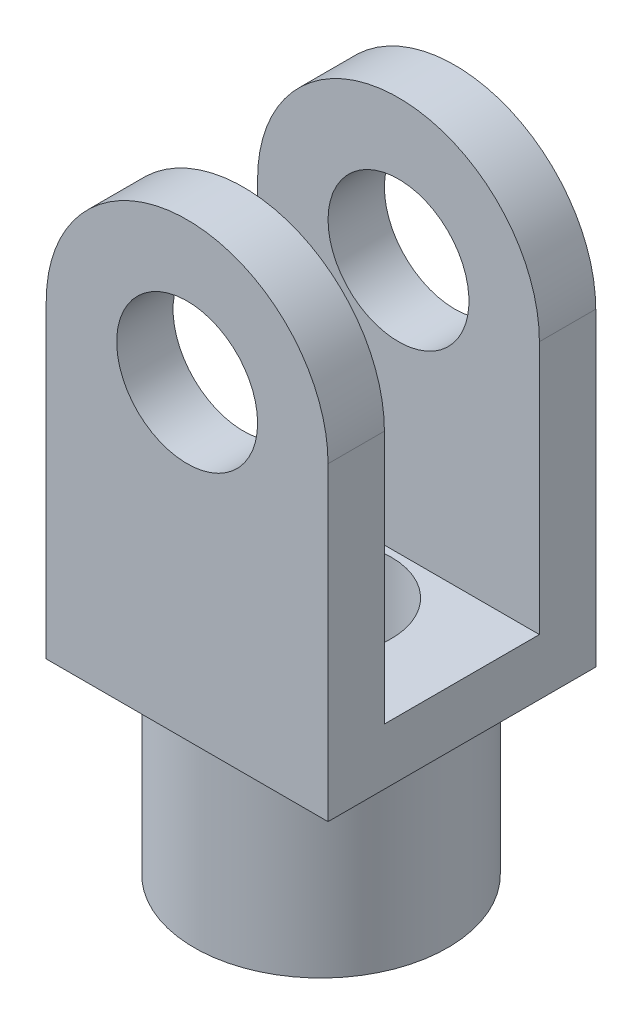
SolidWorks part; units mm, degrees
ref_plane "Plan de face" through (0, 0, 0) normal (0, 0, 1) x (1, 0, 0)
ref_plane "Plan de dessus" through (0, 0, 0) normal (0, 1, 0) x (1, 0, 0)
ref_plane "Plan de droite" through (0, 0, 0) normal (1, 0, 0) x (0, 0, -1)
sketch "Esquisse1" plane through (0, 0, 0) normal (0, 0, 1) x (1, 0, 0)
  line L1 (0, 0) -> (20, 0)
  line L2 (0, 0) -> (0, 22)
  line L4 (20, 0) -> (20, 22)
  circle A0 centre (10, 22) radius 10
  circle A1 centre (10, 22) radius 5
  point P8 (10, 0)
  dimension "D3" = 22
  dimension "D4" = 20
  dimension "D1" = 10
  dimension "D2" = 20
extrude "Boss.-Extru.1" add sketch "Esquisse1" along normal blind 19 contours A0 L2 L1 L4 | A0 A1
sketch "Esquisse2" plane through (0, 0, 0) normal (0, -1, 0) x (1, 0, 0)
  line L1 (0, 15) -> (20, 15)
  line L2 (0, 15) -> (0, 4)
  line L3 (0, 4) -> (20, 4)
  line L4 (20, 15) -> (20, 4)
  line L8 (0, 0) -> (20, 0) construction
  line L9 (0, 19) -> (20, 19) construction
  line L10 (20, 19) -> (20, 0) construction
  line L11 (0, 19) -> (0, 0) construction
  point P10 (10, 19)
  dimension "D1" = 4
  dimension "D2" = 4
extrude "Enlèv. mat.-Extru.1" cut sketch "Esquisse2" against normal through all from offset 4 offset against normal yes
sketch "Esquisse3" plane through (0, 0, 0) normal (0, -1, 0) x (1, 0, 0)
  line L0 (10, 19) -> (10, 0) construction
  line L1 (0, 19) -> (20, 19) construction
  line L2 (0, 0) -> (20, 0) construction
  circle A0 centre (10, 9.5) radius 5
  point P8 (10, 9.5)
  dimension "D1" = 10
extrude "Enlèv. mat.-Extru.2" cut sketch "Esquisse3" against normal through all
sketch "Esquisse4" plane through (0, 0, 0) normal (0, -1, 0) x (1, 0, 0)
  circle A0 centre (10, 9.5) radius 9
  circle A1 centre (10, 9.5) radius 5 construction
  circle A2 centre (10, 9.5) radius 5
  dimension "D1" = 18
extrude "Boss.-Extru.2" add sketch "Esquisse4" along normal blind 13
